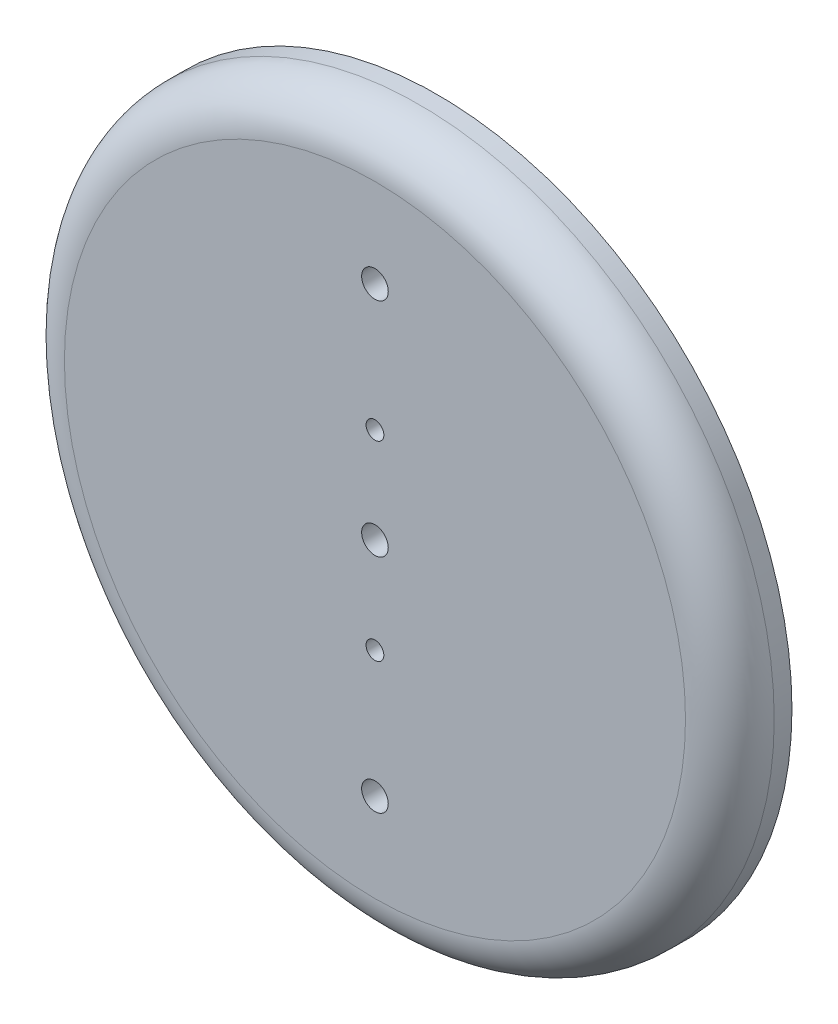
SolidWorks part; units mm, degrees
ref_plane "Piano frontale" through (0, 0, 0) normal (0, 0, 1) x (1, 0, 0)
ref_plane "Piano superiore" through (0, 0, 0) normal (0, 1, 0) x (1, 0, 0)
ref_plane "Piano destro" through (0, 0, 0) normal (1, 0, 0) x (0, 0, -1)
sketch "Schizzo1" plane through (0, 0, 0) normal (0, 0, 1) x (1, 0, 0)
  circle A0 centre (0, 0) radius 40
  dimension "D1" = 80
extrude "Estrusione-Estrusione1" add sketch "Schizzo1" along normal blind 7
fillet "Raccordo1" radius 5 1 edges at (40, 0, 7)
sketch "Schizzo2" plane through (0, 0, 7) normal (0, 0, 1) x (1, 0, 0)
  line L0 (0, 0) -> (0, 35) construction
  line L1 (0, 0) -> (35, 0) construction
  circle A0 centre (0, 0) radius 35 construction
  circle A3 centre (0, 25) radius 1.5
  circle A4 centre (0, -25) radius 1.5
  dimension "D1" = 3
  dimension "D2" = 25
extrude "Taglio-Estrusione1" cut sketch "Schizzo2" against normal blind 37
sketch "Schizzo3" plane through (0, 0, 7) normal (0, 0, 1) x (1, 0, 0)
  line L0 (0, 0) -> (0, 35) construction
  line L1 (0, 0) -> (17.6117, 0) construction
  circle A0 centre (0, 0) radius 35 construction
  circle A1 centre (0, 10.75) radius 1
  circle A2 centre (0, -10.75) radius 1
  dimension "D1" = 2
  dimension "D2" = 10.75
extrude "Taglio-Estrusione2" cut sketch "Schizzo3" against normal blind 10
sketch "Schizzo4" plane through (0, 0, 7) normal (0, 0, 1) x (1, 0, 0)
  circle A0 centre (0, 0) radius 1.5
  dimension "D1" = 3
extrude "Taglio-Estrusione3" cut sketch "Schizzo4" against normal blind 10
